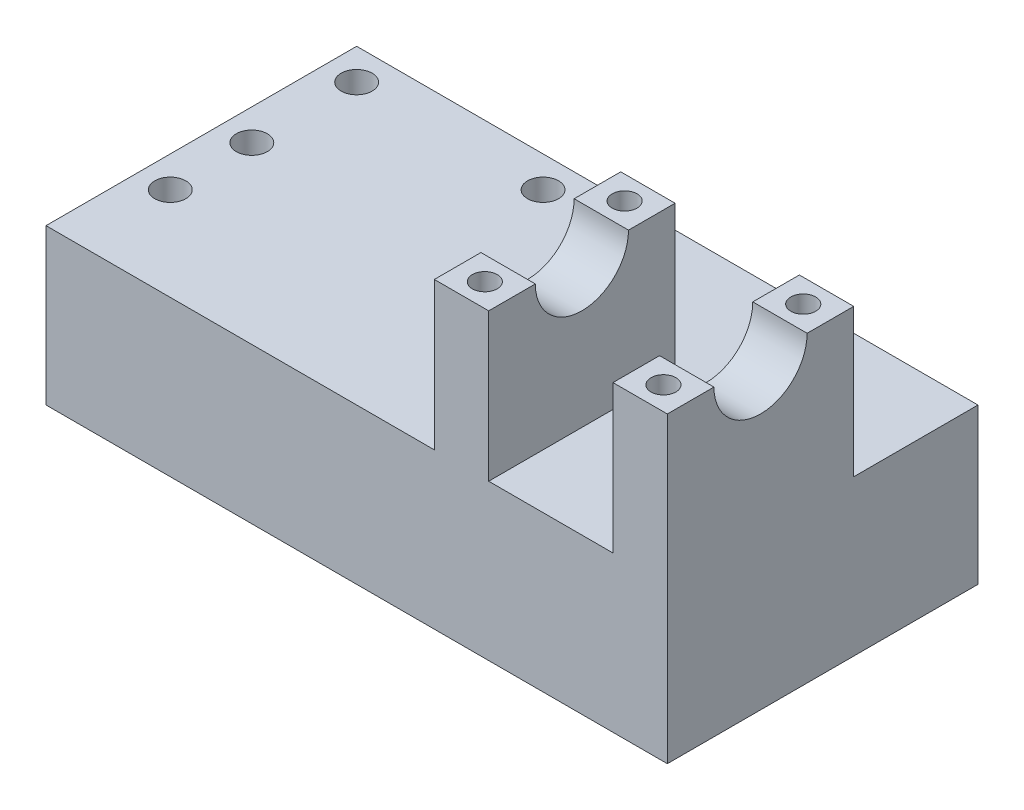
SolidWorks part; units mm, degrees
ref_plane "前视基准面" through (0, 0, 0) normal (0, 0, 1) x (1, 0, 0)
ref_plane "上视基准面" through (0, 0, 0) normal (0, 1, 0) x (1, 0, 0)
ref_plane "右视基准面" through (0, 0, 0) normal (1, 0, 0) x (0, 0, -1)
other "Configuration Table"
sketch "草图1" plane through (0, 0, 0) normal (0, 1, 0) x (1, 0, 0)
  line L1 (0, 0) -> (80, 0)
  line L2 (0, 0) -> (0, -40)
  line L3 (0, -40) -> (80, -40)
  line L4 (80, 0) -> (80, -40)
  dimension "D1" = 80
  dimension "D2" = 40
extrude "凸台-拉伸1" add sketch "草图1" along normal blind 20
hole_wizard "M3 六角圆柱头螺钉的柱形沉头孔1" positions "草图4" profile "草图5" counterbore size "M3" standard "GB" end condition through all
sketch "草图4" plane through (0, 0, 0) normal (0, -1, 0) x (-1, 0, 0)
  line L0 (-80, 0) -> (0, 0) construction
  line L1 (0, 0) -> (0, -40) construction
  point P0 (-4, -4)
  point P2 (-4, -17.5)
  point P4 (-4, -28)
  point P17 (-28, -4)
  dimension "D1" = 4
  dimension "D2" = 13.5
  dimension "D3" = 10.5
  dimension "D4" = 4
  dimension "D5" = 24
sketch "草图5" plane through (4, 0, 4) normal (1, 0, 0) x (0, 0, -1)
  line L0 (0, 0) -> (0, 20)
  line L1 (0, 20) -> (2, 20)
  line L3 (2, 20) -> (2, 7)
  line L4 (2, 7) -> (3.5, 7)
  line L5 (3.5, 7) -> (3.5, 0)
  line L7 (3.5, 0) -> (0, 0)
  line L11 (0, -6.35) -> (0, 107.95) construction
  dimension "通孔孔直径" = 4
  dimension "通孔孔深度" = 20
  dimension "柱形沉头孔直径" = 7
  dimension "柱形沉头孔深度" = 7
sketch "草图6" plane through (0, 20, 0) normal (0, 1, 0) x (1, 0, 0)
  line L0 (0, 0) -> (0, -40) construction
  line L1 (50, -16) -> (57, -16)
  line L2 (50, -16) -> (50, -40)
  line L3 (50, -40) -> (57, -40)
  line L4 (57, -16) -> (57, -40)
  line L5 (73, -16) -> (80, -16)
  line L6 (73, -16) -> (73, -40)
  line L7 (73, -40) -> (80, -40)
  line L8 (80, -16) -> (80, -40)
  line L9 (80, -40) -> (80, 0) construction
  line L10 (0, -40) -> (80, -40) construction
  dimension "D1" = 7
  dimension "D2" = 24
  dimension "D3" = 7
  dimension "D5" = 16
  dimension "D6" = 50
extrude "凸台-拉伸2" add sketch "草图6" along normal blind 19
sketch "草图7" plane through (50, 0, 0) normal (-1, 0, 0) x (0, 0, 1)
  line L0 (16, 39) -> (40, 39) construction
  line L1 (0, 20) -> (0, 0) construction
  circle A0 centre (28, 39) radius 6
  dimension "D1" = 12
  dimension "D2" = 28
extrude "切除-拉伸1" cut sketch "草图7" against normal up to surface (30 mm away) up to face at (80, 19.6667, 18.6667)
sketch "草图16" plane through (0, 39, 0) normal (0, 1, 0) x (1, 0, 0)
  line L0 (50, -19) -> (93.7149, -19) construction
  line L1 (50, -16) -> (50, -22) construction
  line L2 (50, -37) -> (86.2655, -37) construction
  line L3 (50, -34) -> (50, -40) construction
  line L4 (53.5, -16) -> (53.5, -43.1233) construction
  line L5 (57, -16) -> (50, -16) construction
  line L6 (76.5, -16) -> (76.5, -44.5352) construction
  line L7 (80, -16) -> (73, -16) construction
  circle A0 centre (53.5, -37) radius 1.6
  circle A1 centre (53.5, -19) radius 1.6
  circle A2 centre (76.5, -19) radius 1.6
  circle A3 centre (76.5, -37) radius 1.6
  point P24 (0, 0)
  point P25 (0, 0)
  point P26 (0, 0)
  point P27 (0, 0)
  dimension "D1" = 3.2
extrude "切除-拉伸2" cut sketch "草图16" along direction (0, 1, 0) on the side against the normal up to surface (39 mm away)
sketch "草图17" plane through (0, 0, 0) normal (0, -1, 0) x (1, 0, 0)
  line L1 (56.7332, 37) -> (55.1166, 39.8)
  line L2 (55.1166, 39.8) -> (51.8834, 39.8)
  line L3 (51.8834, 39.8) -> (50.2668, 37)
  line L4 (50.2668, 37) -> (51.8834, 34.2)
  line L5 (51.8834, 34.2) -> (55.1166, 34.2)
  line L6 (55.1166, 34.2) -> (56.7332, 37)
  line L7 (73.2668, 37.0059) -> (74.8783, 34.2029)
  line L8 (74.8783, 34.2029) -> (78.1115, 34.1971)
  line L9 (78.1115, 34.1971) -> (79.7332, 36.9941)
  line L10 (79.7332, 36.9941) -> (78.1217, 39.7971)
  line L11 (78.1217, 39.7971) -> (74.8885, 39.8029)
  line L12 (74.8885, 39.8029) -> (73.2668, 37.0059)
  line L13 (56.7332, 18.9988) -> (55.1176, 21.7994)
  line L14 (55.1176, 21.7994) -> (51.8845, 21.8006)
  line L15 (51.8845, 21.8006) -> (50.2668, 19.0012)
  line L16 (50.2668, 19.0012) -> (51.8824, 16.2006)
  line L17 (51.8824, 16.2006) -> (55.1155, 16.1994)
  line L18 (55.1155, 16.1994) -> (56.7332, 18.9988)
  line L19 (79.7332, 18.9925) -> (78.1231, 21.7962)
  line L20 (78.1231, 21.7962) -> (74.8899, 21.8038)
  line L21 (74.8899, 21.8038) -> (73.2668, 19.0075)
  line L22 (73.2668, 19.0075) -> (74.8769, 16.2038)
  line L23 (74.8769, 16.2038) -> (78.1101, 16.1962)
  line L24 (78.1101, 16.1962) -> (79.7332, 18.9925)
  circle A0 centre (53.5, 19) radius 1.6 construction
  circle A1 centre (76.5, 19) radius 1.6 construction
  circle A2 centre (76.5, 37) radius 1.6 construction
  circle A3 centre (53.5, 37) radius 1.6 construction
  circle A4 centre (53.5, 19) radius 1.6 construction
  circle A5 centre (76.5, 19) radius 1.6 construction
  circle A6 centre (76.5, 37) radius 1.6 construction
  circle A7 centre (53.5, 37) radius 1.6 construction
  circle A8 centre (53.5, 37) radius 2.8 construction
  circle A9 centre (76.5, 37) radius 2.8 construction
  circle A10 centre (53.5, 19) radius 2.8 construction
  circle A11 centre (76.5, 19) radius 2.8 construction
  point P12 (0, 0)
  dimension "D1" = 5.6
extrude "切除-拉伸3" cut sketch "草图17" against normal blind 6
